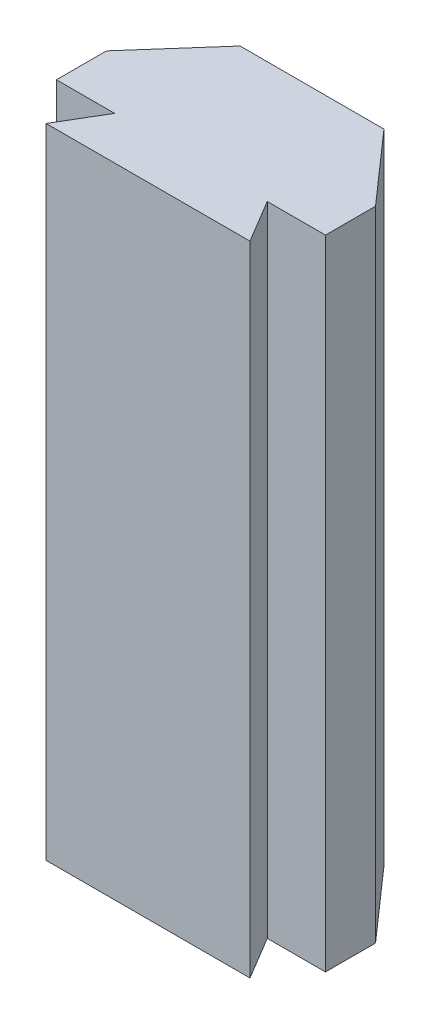
SolidWorks part; units mm, degrees
ref_plane "Front Plane" through (0, 0, 0) normal (0, 0, 1) x (1, 0, 0)
ref_plane "Top Plane" through (0, 0, 0) normal (0, 1, 0) x (1, 0, 0)
ref_plane "Right Plane" through (0, 0, 0) normal (1, 0, 0) x (0, 0, -1)
sketch "Sketch7" plane through (0, 0, 0) normal (0, 1, 0) x (1, 0, 0)
  line L0 (-5.1906, 5.6744) -> (0.5594, 5.6744)
  line L1 (0.5594, 5.6744) -> (3.0594, 2.8376)
  line L2 (3.0594, 2.8376) -> (3.0594, 0.8376)
  line L3 (3.0594, 0.8376) -> (0.7344, 0.8376)
  line L4 (0.7344, 0.8376) -> (1.7594, -0.8798)
  line L5 (1.7594, -0.8798) -> (-6.3858, -0.8826)
  line L6 (-6.3858, -0.8826) -> (-5.3656, 0.8376)
  line L7 (-5.3656, 0.8376) -> (-7.6906, 0.8376)
  line L8 (-7.6906, 0.8376) -> (-7.6906, 2.8376)
  line L9 (-7.6906, 2.8376) -> (-5.1906, 5.6744)
  point P7 (0, 0)
  point P11 (0, 0)
  dimension "D2" = 10.75
  dimension "D3" = 2
  dimension "D4" = 2.5
  dimension "D5" = 2.5
  dimension "D6" = 5.75
  dimension "D7" = 2.325
  dimension "D8" = 3.7812
  dimension "D9" = 2.325
  dimension "D10" = 2
  dimension "D11" = 4.8368
  dimension "D12" = 2
  dimension "D13" = 8.1452
extrude "Boss-Extrude4" add sketch "Sketch7" along normal blind 25.5
